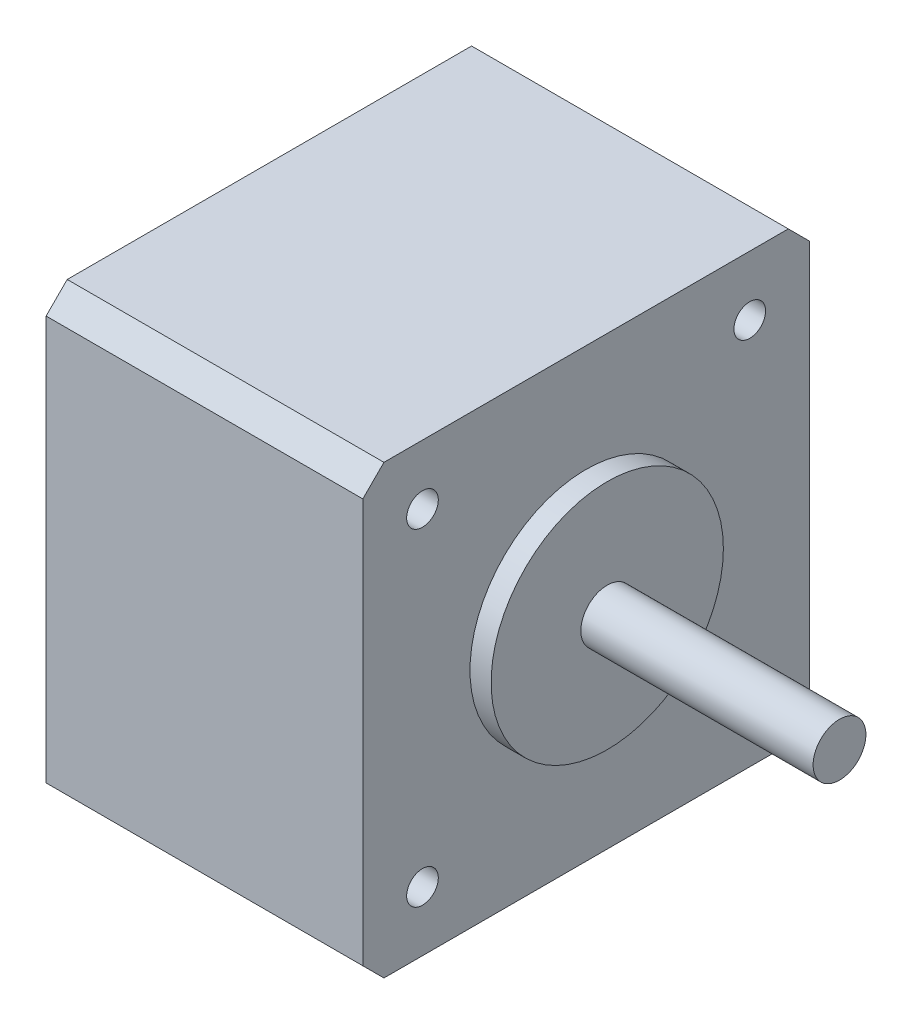
SolidWorks part; units mm, degrees
ref_plane "前视基准面" through (0, 0, 0) normal (0, 0, 1) x (1, 0, 0)
ref_plane "上视基准面" through (0, 0, 0) normal (0, 1, 0) x (1, 0, 0)
ref_plane "右视基准面" through (0, 0, 0) normal (1, 0, 0) x (0, 0, -1)
sketch "草图1" plane through (0, 0, 0) normal (1, 0, 0) x (0, 0, -1)
  line L1 (21.15, -21.15) -> (-21.15, -21.15)
  line L2 (21.15, -21.15) -> (21.15, 21.15)
  line L3 (21.15, 21.15) -> (-21.15, 21.15)
  line L4 (-21.15, -21.15) -> (-21.15, 21.15)
  line L5 (21.15, -21.15) -> (-21.15, 21.15) construction
  line L6 (21.15, 21.15) -> (-21.15, -21.15) construction
  point P0 (0, 0)
  dimension "D1" = 42.3
extrude "凸台-拉伸1" add sketch "草图1" along normal blind 30
chamfer "倒角1" distance 2 angle 45 4 edges at (15, -21.15, 21.15) (15, -21.15, -21.15) (15, 21.15, -21.15) (15, 21.15, 21.15)
sketch "草图2" plane through (30, 0, 0) normal (1, 0, 0) x (0, 0, -1)
  line L0 (-21.15, 19.15) -> (-21.15, 15.5) construction
  line L1 (-21.15, 19.15) -> (-21.15, -19.15) construction
  line L2 (-21.15, 15.5) -> (-15.5, 15.5) construction
  circle A0 centre (-15.5, 15.5) radius 1.5
  circle A1 centre (15.5, 15.5) radius 1.5
  circle A2 centre (15.5, -15.5) radius 1.5
  circle A3 centre (-15.5, -15.5) radius 1.5
  point P16 (0, 0)
  dimension "D3" = 4
  dimension "D1" = 3.65
  dimension "D2" = 5.65
extrude "切除-拉伸1" cut sketch "草图2" against normal blind 3
sketch "草图3" plane through (30, 0, 0) normal (1, 0, 0) x (0, 0, -1)
  circle A0 centre (0, 0) radius 11
extrude "凸台-拉伸2" add sketch "草图3" along normal blind 2
sketch "草图4" plane through (32, 0, 0) normal (1, 0, 0) x (0, 0, -1)
  circle A0 centre (0, 0) radius 2.5
extrude "凸台-拉伸3" add sketch "草图4" along normal blind 22
